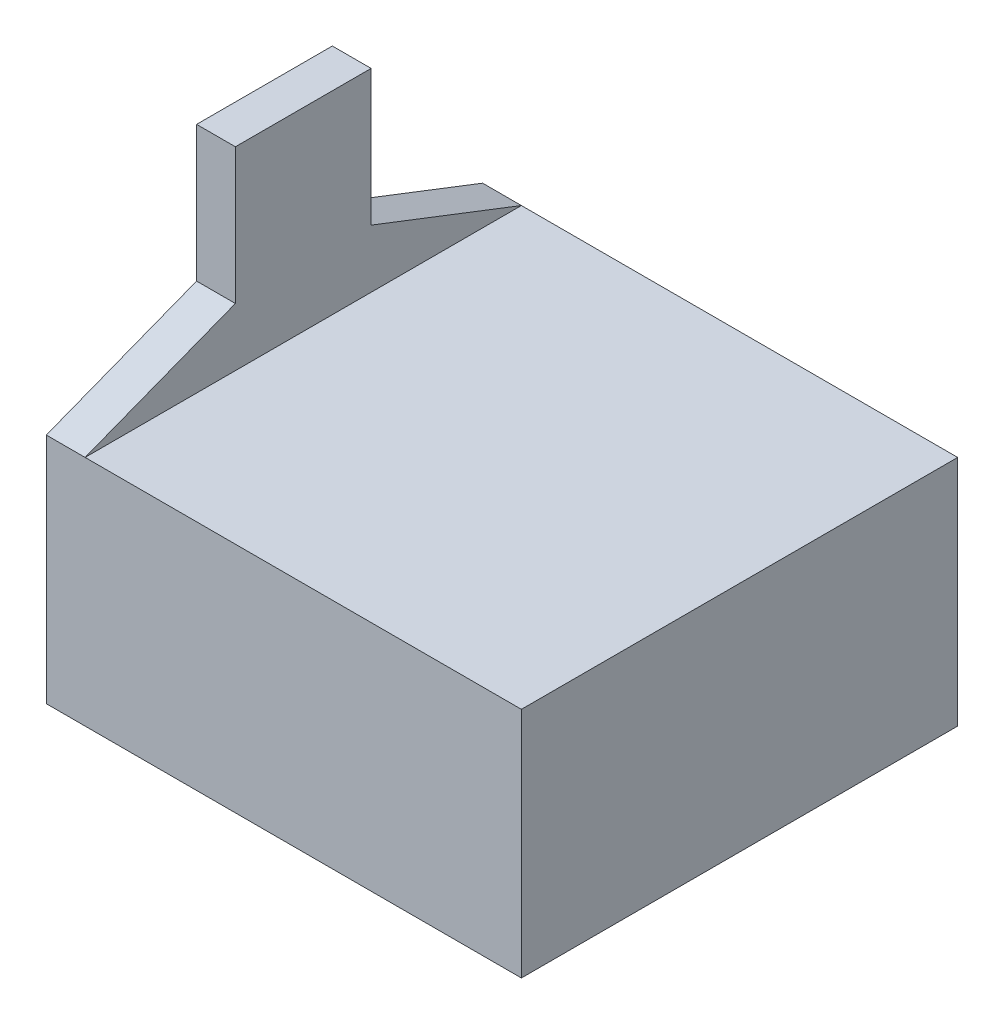
SolidWorks part; units mm, degrees
ref_plane "Front Plane" through (0, 0, 0) normal (0, 0, 1) x (1, 0, 0)
ref_plane "Top Plane" through (0, 0, 0) normal (0, 1, 0) x (1, 0, 0)
ref_plane "Right Plane" through (0, 0, 0) normal (1, 0, 0) x (0, 0, -1)
sketch "Sketch1" plane through (0, 0, 0) normal (1, 0, 0) x (0, 0, -1)
  line L0 (-11.25, 0) -> (11.25, 0)
  line L1 (11.25, 0) -> (11.25, 12)
  line L2 (11.25, 12) -> (3.5, 15)
  line L3 (3.5, 15) -> (3.5, 22)
  line L4 (3.5, 22) -> (-3.5, 22)
  line L5 (-3.5, 22) -> (-3.5, 15)
  line L6 (-3.5, 15) -> (-11.25, 12)
  line L7 (-11.25, 12) -> (-11.25, 0)
  dimension "D1" = 12
  dimension "D2" = 3
  dimension "D3" = 7
  dimension "D4" = 7
  dimension "D5" = 22.5
extrude "Boss-Extrude1" add sketch "Sketch1" along normal blind 2
sketch "Sketch2" plane through (2, 0, 0) normal (1, 0, 0) x (0, 0, -1)
  line L2 (-11.25, 0) -> (11.25, 0)
  line L3 (-11.25, 0) -> (-11.25, 12)
  line L4 (-11.25, 12) -> (11.25, 12)
  line L5 (11.25, 0) -> (11.25, 12)
extrude "Boss-Extrude2" add sketch "Sketch2" along normal blind 22.5 contours L3 L2 L5 L4
